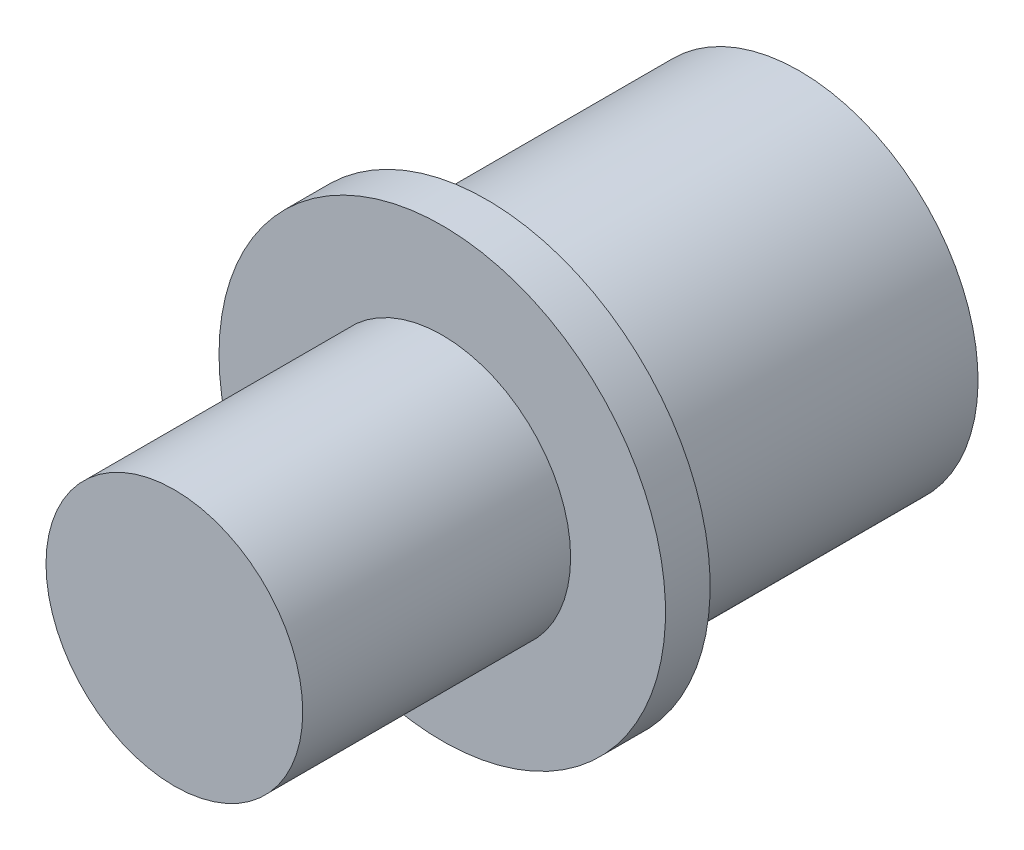
SolidWorks part; units mm, degrees
ref_plane "Front Plane" through (0, 0, 0) normal (0, 0, 1) x (1, 0, 0)
ref_plane "Top Plane" through (0, 0, 0) normal (0, 1, 0) x (1, 0, 0)
ref_plane "Right Plane" through (0, 0, 0) normal (1, 0, 0) x (0, 0, -1)
sketch "Sketch13" plane through (0, 5, 0) normal (0, 0, -1) x (1, 0, 0)
  circle A0 centre (0, 5) radius 5
  dimension "D1" = 10
extrude "Boss-Extrude5" add sketch "Sketch13" along normal blind 1
sketch "Sketch14" plane through (0, 0, -1) normal (0, 0, -1) x (1, 0, 0)
  circle A0 centre (0, 0) radius 4
  dimension "D1" = 8
extrude "Boss-Extrude6" add sketch "Sketch14" along normal blind 7
sketch "Sketch15" plane through (0, 0, -8) normal (0, 0, -1) x (1, 0, 0)
  circle A0 centre (0, 0) radius 2.5
  dimension "D1" = 5
extrude "Cut-Extrude5" cut sketch "Sketch15" against normal blind 3
sketch "Sketch16" plane through (0, 0, 0) normal (0, 0, 1) x (1, 0, 0)
  circle A0 centre (0, 0) radius 2.875
  dimension "D1" = 5.75
extrude "Boss-Extrude7" add sketch "Sketch16" along normal blind 6
